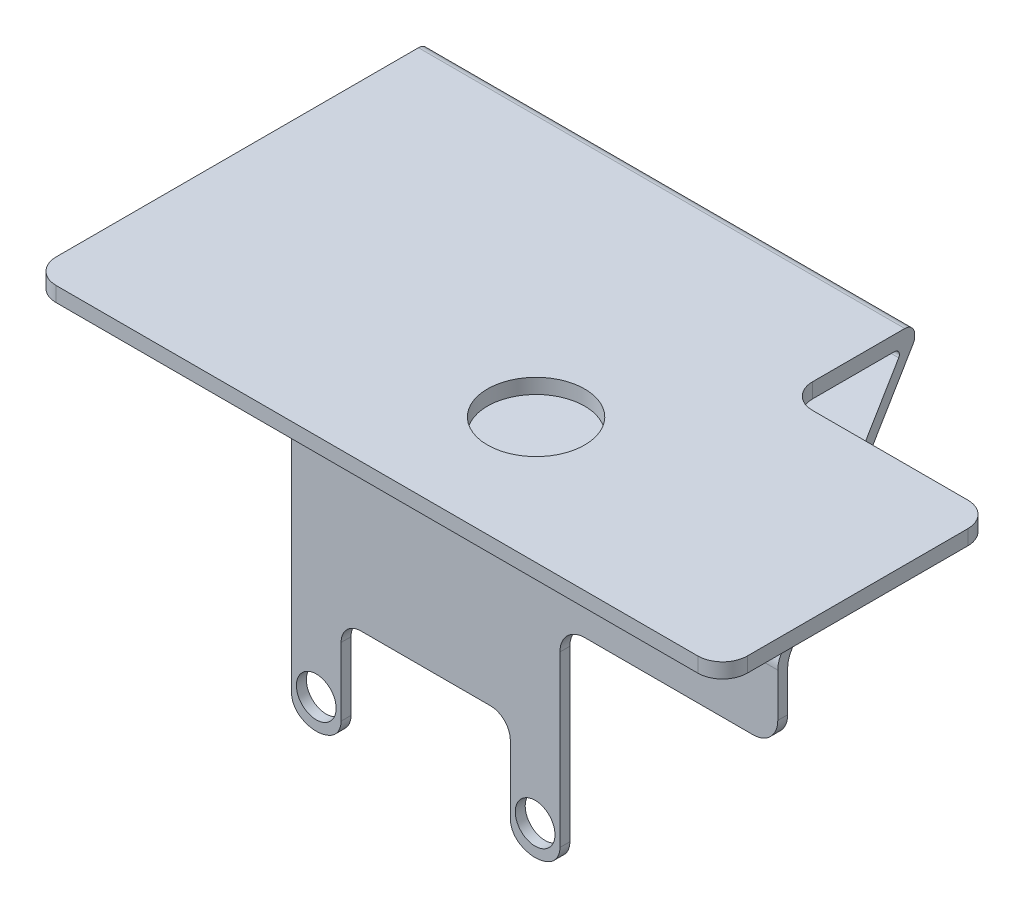
SolidWorks part; units mm, degrees
ref_plane "Front Plane" through (0, 0, 0) normal (0, 0, 1) x (1, 0, 0)
ref_plane "Top Plane" through (0, 0, 0) normal (0, 1, 0) x (1, 0, 0)
ref_plane "Right Plane" through (0, 0, 0) normal (1, 0, 0) x (0, 0, -1)
sketch "Sketch1" plane through (0, 0, 0) normal (0, 1, 0) x (1, 0, 0)
  line L0 (-33.0067, 26.3976) -> (19.1433, 26.3976) construction
  line L1 (-32.322, -13.6024) -> (32.322, -13.6024)
  line L2 (-34.822, -11.1024) -> (-34.822, 13.6024)
  line L3 (16.678, 13.6024) -> (32.322, 13.6024)
  line L4 (34.822, -11.1024) -> (34.822, 11.1024)
  line L5 (-34.822, -13.6024) -> (34.822, 13.6024) construction
  line L6 (-34.822, 13.6024) -> (34.822, -13.6024) construction
  line L7 (14.178, 43.9587) -> (14.178, 25.3597) construction
  line L8 (-34.822, -11.1024) -> (-34.822, -13.6024)
  line L9 (-34.822, 13.6024) -> (14.178, 13.6024)
  line L10 (-34.822, 13.6024) -> (-34.822, 23.8976)
  line L11 (-32.322, 26.3976) -> (14.178, 26.3976)
  line L12 (14.178, 16.1024) -> (14.178, 26.3976)
  line L13 (-34.822, -13.6024) -> (-32.322, -13.6024)
  line L14 (-32.322, 26.3976) -> (-34.822, 26.3976)
  line L15 (-34.822, 26.3976) -> (-34.822, 23.8976)
  circle A0 centre (3.322, -0.8976) radius 4.8968
  arc A3 (32.322, -13.6024) -> (34.822, -11.1024) centre (32.322, -11.1024) ccw
  arc A4 (32.322, 13.6024) -> (34.822, 11.1024) centre (32.322, 11.1024) cw
  arc A5 (16.678, 13.6024) -> (14.178, 16.1024) centre (16.678, 16.1024) cw
  point P0 (0, 0)
  dimension "D1" = 14.5
  dimension "D2" = 31.5
  dimension "D3" = 40
  dimension "D4" = 49
extrude "Boss-Extrude1" add sketch "Sketch1" along normal blind 1.5
ref_plane "Plane1" through (14.178, 0, 0) normal (1, 0, 0) x (0, 0, -1)
sketch "Sketch2" plane through (14.178, 0, 0) normal (1, 0, 0) x (0, 0, -1)
  line L0 (20.057, -30.5) -> (15.9456, -30.5) construction
  line L1 (16.1024, 1.5) -> (26.3976, 1.5) construction
  line L2 (22.0519, -21.5) -> (11.4271, -21.5) construction
  line L3 (25.234, 0) -> (12.954, -20.634)
  line L4 (13.6024, 0.75) -> (13.6024, -28.8027) construction
  line L5 (13.6024, 1.5) -> (13.6024, 0) construction
  line L7 (26.3976, 0) -> (13.954, -20.9091)
  line L8 (13.6024, -22.1876) -> (13.6024, -28.8027)
  line L9 (12.6024, -21.9126) -> (12.6024, -28.8027)
  line L10 (13.6024, -28.8027) -> (12.6024, -28.8027)
  line L11 (26.3976, 0) -> (25.234, 0)
  line L12 (16.1024, 0) -> (26.3976, 0) construction
  line L13 (25.5383, 0.5114) -> (12.6024, -21.2249) construction
  line L14 (12.6024, -21.2249) -> (12.6024, -28.8027) construction
  line L15 (13.6024, -21.5) -> (13.6024, -28.8027) construction
  line L16 (26.3976, 0) -> (13.6024, -21.5) construction
  arc A0 (12.954, -20.634) -> (12.6024, -21.9126) centre (15.1024, -21.9126) ccw
  arc A1 (13.6024, -22.1876) -> (13.954, -20.9091) centre (16.1024, -22.1876) cw
  point P25 (13.6024, -21.5)
  dimension "D4" = 2.5
  dimension "D1" = 32
  dimension "D2" = 23
  dimension "D3" = 1
extrude "Boss-Extrude4" add sketch "Sketch2" against normal up to vertex (49 mm away)
fillet "Fillet1" radius 1 2 edges at (-10.322, 1.5, -26.3976) (-10.322, 0, -26.3976)
fillet "Fillet2" radius 0.5 1 edges at (-10.322, 0, -25.234)
sketch "Sketch3" plane through (0, 0, -12.6024) normal (0, 0, 1) x (1, 0, 0)
  line L0 (-34.822, -28.8027) -> (-34.822, -34.112) construction
  line L1 (-7.772, -28.8027) -> (-7.772, -39.5) construction
  line L2 (-34.822, -28.8027) -> (14.178, -28.8027) construction
  line L3 (-12.772, -39.5) -> (-14.8392, -39.5) construction
  line L4 (-34.822, 1.5) -> (32.322, 1.5) construction
  line L5 (-7.772, -39.5) -> (-7.772, -48.366) construction
  line L6 (-14.772, -39.5) -> (-27.822, -39.5)
  line L7 (-7.772, -39.5) -> (-7.772, -28.8027)
  line L8 (-7.772, -28.8027) -> (-34.822, -28.8027)
  line L9 (-34.822, -39.5) -> (-34.822, -28.8027)
  line L10 (-12.772, -41.5) -> (-12.772, -48.366)
  line L11 (-7.772, -49.1583) -> (-7.772, -39.5)
  line L12 (-7.772, -39.5) -> (-7.772, -50.5) construction
  line L13 (-12.772, -39.5) -> (-12.772, -50.5) construction
  line L14 (-21.297, -39.5) -> (-21.297, -44.8944) construction
  line L15 (-34.822, -39.5) -> (-34.822, -48.366) construction
  line L16 (-34.822, -49.1583) -> (-34.822, -39.5)
  line L17 (-29.822, -41.5) -> (-29.822, -48.366)
  circle A1 centre (-10.272, -47.5) radius 2
  arc A2 (-11.772, -50.0981) -> (-8.772, -50.0981) centre (-10.272, -47.5) ccw
  arc A3 (-8.772, -50.0981) -> (-7.772, -48.366) centre (-9.772, -48.366) ccw
  arc A4 (-11.772, -50.0981) -> (-12.772, -48.366) centre (-10.772, -48.366) cw
  arc A5 (-30.822, -50.0981) -> (-29.822, -48.366) centre (-31.822, -48.366) ccw
  arc A6 (-33.822, -50.0981) -> (-34.822, -48.366) centre (-32.822, -48.366) cw
  arc A7 (-30.822, -50.0981) -> (-33.822, -50.0981) centre (-32.322, -47.5) cw
  circle A8 centre (-32.322, -47.5) radius 2
  arc A9 (-29.822, -41.5) -> (-27.822, -39.5) centre (-27.822, -41.5) cw
  arc A10 (-12.772, -41.5) -> (-14.772, -39.5) centre (-14.772, -41.5) ccw
  point P37 (-29.822, -39.5)
  line M18 (-34.822, -28.8027) -> (14.178, -28.8027)
  dimension "D5" = 2.5
  dimension "D6" = 2
  dimension "D4" = 2
  dimension "D1" = 27.05
  dimension "D2" = 41
  dimension "D7" = 2.5
  dimension "D3" = 5
extrude "Boss-Extrude6" add sketch "Sketch3" against normal up to surface (1 mm away) contours A10 L10 A4 A2 A3 L11 L7 L9 L16 A6 A7 A5 L17 A9 L6 A1 A8 M18 up to face at (-10.322, -25.4952, -13.6024)
fillet "Fillet3" radius 2.5 2 edges at (-7.772, -28.8027, -13.1024) (14.178, -28.8027, -13.1024)
fillet "Fillet4" radius 2.5 1 edges at (-34.822, 0.75, 13.6024)
